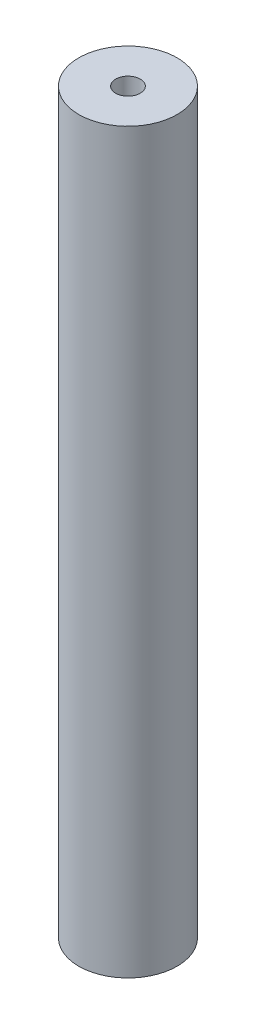
SolidWorks part; units mm, degrees
material "Chrome Stainless Steel"
ref_plane "Front" through (0, 0, 0) normal (0, 0, 1) x (1, 0, 0)
ref_plane "Top" through (0, 0, 0) normal (0, 1, 0) x (1, 0, 0)
ref_plane "Right" through (0, 0, 0) normal (1, 0, 0) x (0, 0, -1)
sketch "Sketch1" plane through (0, 0, 0) normal (0, 1, 0) x (1, 0, 0)
  circle A0 centre (0, 0) radius 12
extrude "Extrude1" add sketch "Sketch1" against normal blind 180
ref_point "Point2"
ref_plane "Plane1" through (0, 0, 0) normal (0, 1, 0) x (-1, 0, 0)
hole_wizard "M6 Tapped Hole1" positions "Sketch5" profile "Sketch4" tap size "M6" standard "ISO"
sketch "Sketch5" plane through (0, 0, 0) normal (0, 1, 0) x (-1, 0, 0)
  point P0 (0, 0)
sketch "Sketch4" plane through (0, 0, 0) normal (1, 0, 0) x (0, 0, 1)
  line L0 (0, 0) -> (0, 16.5022)
  line L1 (0, 16.5022) -> (2.5, 15)
  line L2 (2.5, 15) -> (2.5, 12)
  line L3 (2.5, 12) -> (3, 12)
  line L4 (3, 12) -> (3, 0)
  line L5 (3, 0) -> (0, 0)
  line L10 (0, 16.5022) -> (-2.5, 15) construction
  line L11 (0, -6.35) -> (0, 107.95) construction
  dimension "Tap Drill Dia." = 5
  dimension "Tap Drill Depth" = 15
  dimension "Thread Major Dia." = 6
  dimension "Thread Depth" = 12
  dimension "Drill Angle" = 118
